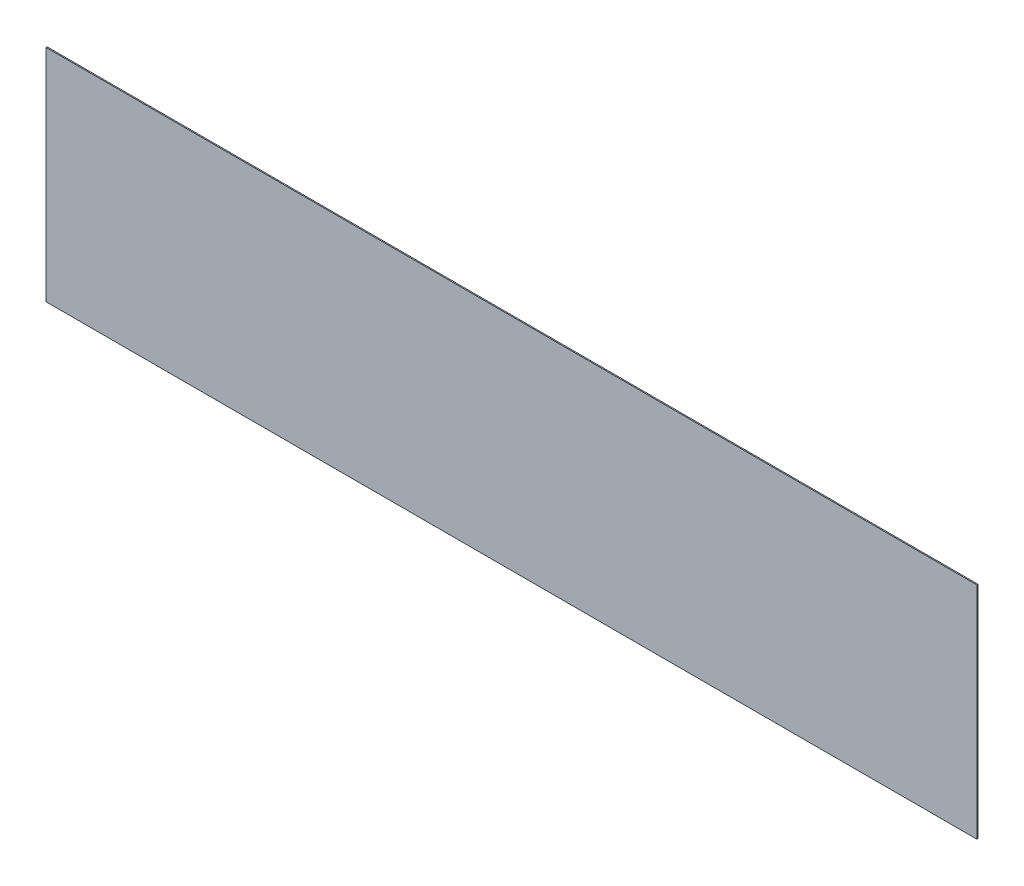
SolidWorks part; units mm, degrees
ref_plane "Front Plane" through (0, 0, 0) normal (0, 0, 1) x (1, 0, 0)
ref_plane "Top Plane" through (0, 0, 0) normal (0, 1, 0) x (1, 0, 0)
ref_plane "Right Plane" through (0, 0, 0) normal (1, 0, 0) x (0, 0, -1)
other "Configuration Table"
sketch "Sketch1" plane through (0, 0, 0) normal (0, 0, 1) x (1, 0, 0)
  line L1 (66, 1670) -> (1334, 1670)
  line L2 (66, 1670) -> (66, 1970)
  line L3 (66, 1970) -> (1334, 1970)
  line L4 (1334, 1670) -> (1334, 1970)
extrude "STORE_panel_sogutma_1" add sketch "Sketch1" along normal blind 1.5 from offset 38.5 separate body
